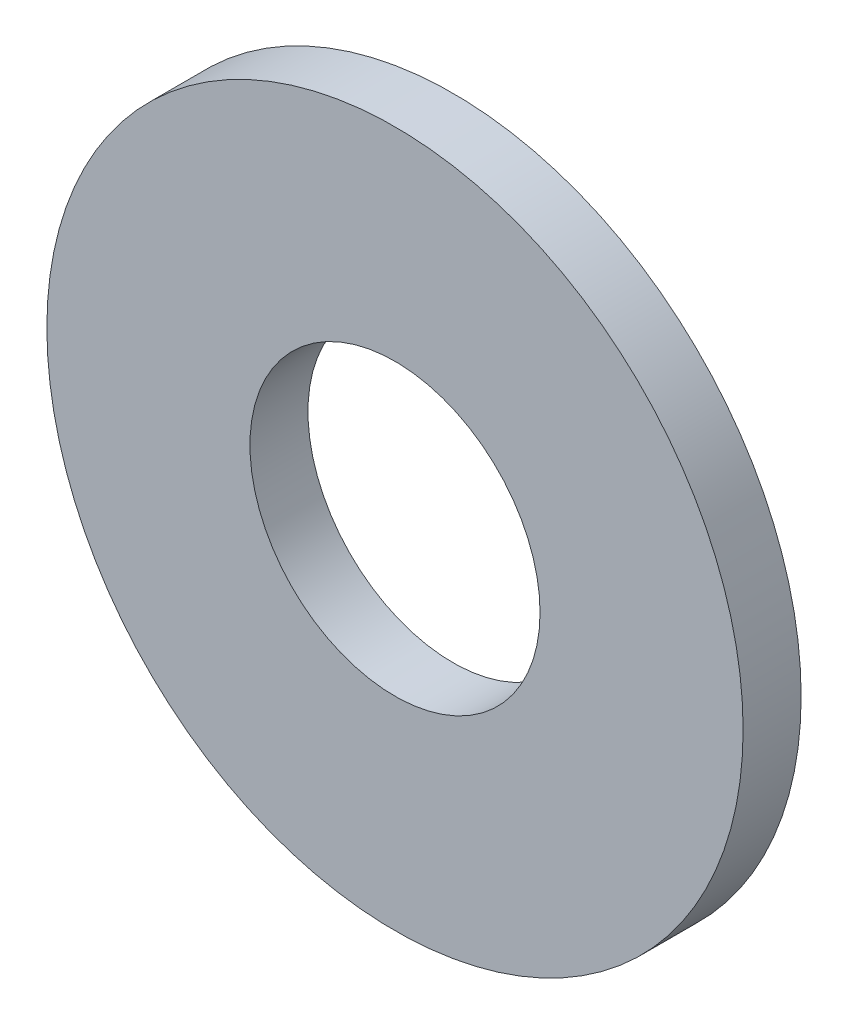
SolidWorks part; units mm, degrees
ref_plane "Front Plane" through (0, 0, 0) normal (0, 0, 1) x (1, 0, 0)
ref_plane "Top Plane" through (0, 0, 0) normal (0, 1, 0) x (1, 0, 0)
ref_plane "Right Plane" through (0, 0, 0) normal (1, 0, 0) x (0, 0, -1)
sketch "Sketch1" plane through (0, 0, 0) normal (0, 0, 1) x (1, 0, 0)
  circle A0 centre (0, 0) radius 2.5
  circle A1 centre (0, 0) radius 6
  dimension "D1" = 5
  dimension "D2" = 12
extrude "Boss-Extrude1" add sketch "Sketch1" along normal blind 1
